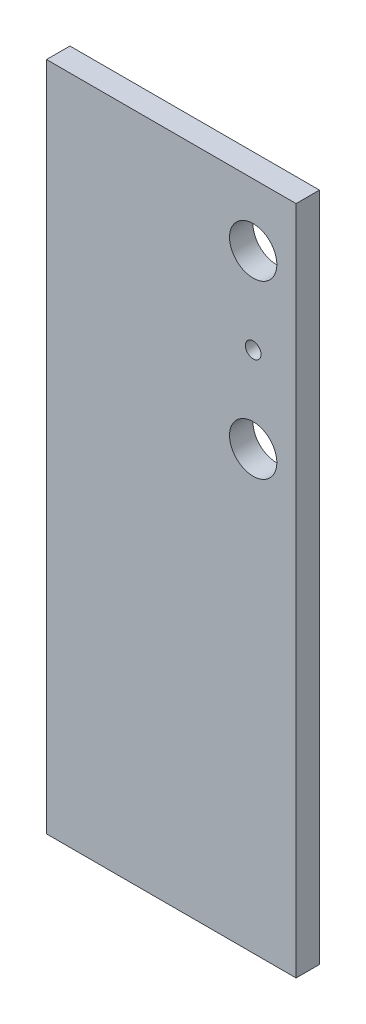
SolidWorks part; units mm, degrees
material "Balsa"
ref_plane "Front Plane" through (0, 0, 0) normal (0, 0, 1) x (1, 0, 0)
ref_plane "Top Plane" through (0, 0, 0) normal (0, 1, 0) x (1, 0, 0)
ref_plane "Right Plane" through (0, 0, 0) normal (1, 0, 0) x (0, 0, -1)
sketch "Sketch1" plane through (0, 0, 0) normal (0, 0, 1) x (1, 0, 0)
  line L1 (0, 0) -> (203.2, 0)
  line L2 (0, 0) -> (0, 546.1)
  line L3 (0, 546.1) -> (203.2, 546.1)
  line L4 (203.2, 0) -> (203.2, 546.1)
  dimension "D1" = 203.2
  dimension "D2" = 546.1
extrude "Boss-Extrude1" add sketch "Sketch1" along normal blind 19.05
sketch "Sketch2" plane through (0, 0, 0) normal (0, 0, -1) x (-1, 0, 0)
  line L0 (-101.6, 546.1) -> (-101.6, 0) construction
  line L1 (-203.2, 546.1) -> (0, 546.1) construction
  line L2 (0, 0) -> (-203.2, 0) construction
  line L3 (-168.275, 546.1) -> (-168.275, 0) construction
  circle A0 centre (-168.275, 495.3) radius 19.2405
  circle A1 centre (-168.275, 355.6) radius 19.2405
  dimension "D1" = 38.481
  dimension "D3" = 50.8
  dimension "D2" = 139.7
  dimension "D4" = 66.675
extrude "Cut-Extrude1" cut sketch "Sketch2" against normal through all
sketch "Esquisse1" plane through (0, 0, 0) normal (0, 0, -1) x (-1, 0, 0)
  line L0 (-168.275, 476.0595) -> (-168.275, 374.8405) construction
  circle A0 centre (-168.275, 425.45) radius 10.9982
  circle A1 centre (-168.275, 495.3) radius 19.2405 construction
  circle A2 centre (-168.275, 355.6) radius 19.2405 construction
  point P9 (-168.275, 425.45)
  dimension "D1" = 21.9964
extrude "Enlèv. mat.-Extru.1" cut sketch "Esquisse1" against normal blind 6.985
sketch "Esquisse2" plane through (0, 0, 6.985) normal (0, 0, -1) x (-1, 0, 0)
  circle A0 centre (-168.275, 425.45) radius 6.35
  dimension "D1" = 12.7
extrude "Enlèv. mat.-Extru.2" cut sketch "Esquisse2" against normal through all
